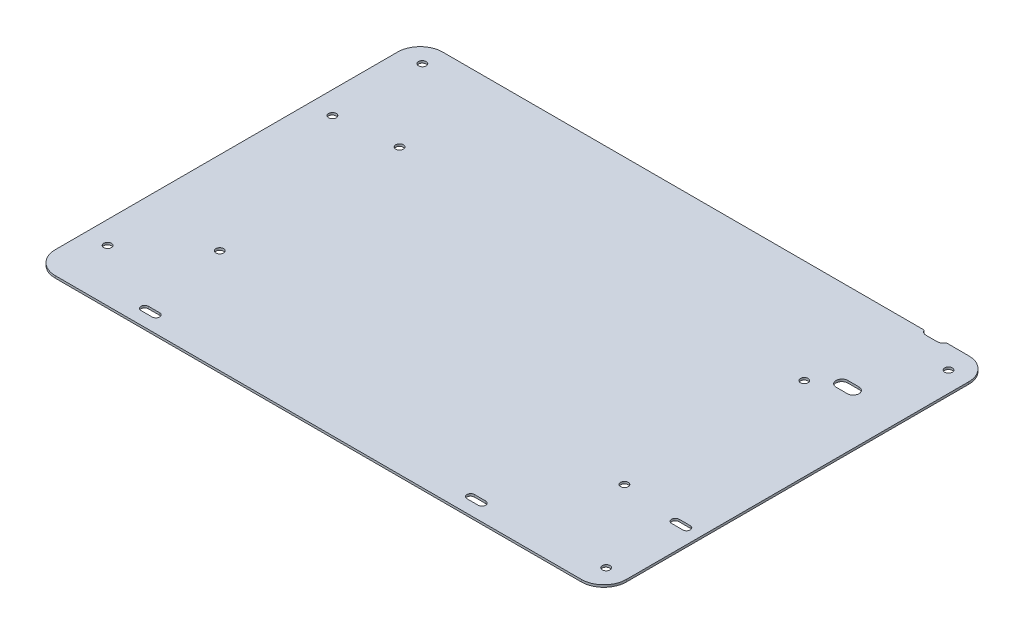
SolidWorks part; units mm, degrees
ref_plane "Front Plane" through (0, 0, 0) normal (0, 0, 1) x (1, 0, 0)
ref_plane "Top Plane" through (0, 0, 0) normal (0, 1, 0) x (1, 0, 0)
ref_plane "Right Plane" through (0, 0, 0) normal (1, 0, 0) x (0, 0, -1)
sketch "Sketch1" plane through (0, 0, 0) normal (0, 1, 0) x (1, 0, 0)
  line L1 (-127, 86.135) -> (127, 86.135)
  line L2 (-127, 86.135) -> (-127, -86.135)
  line L3 (-127, -86.135) -> (127, -86.135)
  line L4 (127, 86.135) -> (127, -86.135)
  line L5 (-127, 86.135) -> (127, -86.135) construction
  line L6 (-127, -86.135) -> (127, 86.135) construction
  point P0 (0, 0)
  dimension "D1" = 254
  dimension "D2" = 172.27
extrude "Boss-Extrude1" add sketch "Sketch1" along normal blind 1
fillet "Fillet1" radius 10 4 edges at (-127, 0.5, 86.135) (127, 0.5, 86.135) (127, 0.5, -86.135) (-127, 0.5, -86.135)
hole_wizard "M3 Clearance Hole1" positions "Sketch2" profile "Sketch3" hole size "M3" standard "ANSI Metric" end condition through all
sketch "Sketch2" plane through (0, 1, 0) normal (0, 1, 0) x (1, 0, 0)
  line L1 (-90, 40) -> (90, 40)
  line L2 (-90, 40) -> (-90, -40)
  line L3 (-90, -40) -> (90, -40)
  line L4 (90, 40) -> (90, -40)
  line L5 (-90, 40) -> (90, -40) construction
  line L6 (-90, -40) -> (90, 40) construction
  line L7 (117, 86.135) -> (-117, 86.135) construction
  line L8 (-127, 76.135) -> (-127, -76.135) construction
  line L9 (-117, -86.135) -> (117, -86.135) construction
  line L10 (127, -76.135) -> (127, 76.135) construction
  point P0 (-117, 77.135)
  point P2 (-117, -62.865)
  point P4 (118, -76.135)
  point P6 (118, 76.135)
  point P8 (-90, -40)
  point P10 (90, -40)
  point P13 (-90, 40)
  point P15 (90, 40)
  point P142 (-117, 37.135)
  dimension "D1" = 180
  dimension "D2" = 80
  dimension "D3" = 9
  dimension "D4" = 10
  dimension "D5" = 10
  dimension "D6" = 23.27
  dimension "D7" = 10
  dimension "D8" = 9
  dimension "D9" = 9
  dimension "D10" = 10
  dimension "D11" = 40
sketch "Sketch3" plane through (-117, 1, -77.135) normal (1, 0, 0) x (0, 0, 1)
  line L0 (0, 0) -> (0, 1)
  line L1 (0, 1) -> (1.7, 1)
  line L2 (1.7, 1) -> (1.7, 0)
  line L5 (1.7, 0) -> (0, 0)
  line L11 (0, -6.35) -> (0, 107.95) construction
  dimension "Thru Hole Dia." = 3.4
  dimension "Thru Hole Depth" = 1
sketch "Sketch4" plane through (0, 1, 0) normal (0, 1, 0) x (1, 0, 0)
  line L0 (-117, 78.835) -> (-114.5685, 78.835)
  line L5 (-117, 75.435) -> (-114.5685, 75.435)
  line L7 (118, 77.835) -> (120.4315, 77.835)
  line L8 (118, 74.435) -> (120.4315, 74.435)
  line L9 (118, -74.435) -> (120.6815, -74.435)
  line L10 (118, -77.835) -> (120.6815, -77.835)
  line L11 (-117, -61.165) -> (-114.5685, -61.165)
  line L12 (-117, -64.565) -> (-114.5685, -64.565)
  circle A1 centre (-117, -62.865) radius 1.7 construction
  circle A3 centre (-112.25, 77.135) radius 2.875
  circle A6 centre (-112.25, -62.865) radius 2.875
  circle A7 centre (123, -76.135) radius 2.875
  circle A8 centre (122.75, 76.135) radius 2.875
  circle A9 centre (-117, 77.135) radius 1.7 construction
  circle A10 centre (118, 76.135) radius 1.7 construction
  circle A11 centre (118, -76.135) radius 1.7 construction
  point P2 (-117, 77.135)
  point P3 (-117, -62.865)
  point P6 (118, -76.135)
  point P10 (118, 76.135)
  circle M1 centre (-117, 77.135) radius 1.7
  circle M2 centre (-117, -62.865) radius 1.7
  circle M3 centre (118, -76.135) radius 1.7
  circle M4 centre (118, 76.135) radius 1.7
  dimension "D2" = 5.75
  dimension "D1" = 4.75
  dimension "D3" = 4.75
  dimension "D4" = 5
  dimension "D5" = 4.75
extrude "Cut-Extrude1" [suppressed] cut sketch "Sketch4" against normal through all contours A3 L0 L5 M1 | A3 | A8 L7 L8 M4 | A8 | A7 L9 L10 M3 | A7 | A6 L11 L12 M2 | A6
sketch "Sketch6" plane through (0, 1, 0) normal (0, 1, 0) x (1, 0, 0)
  line L0 (99.6, 89.735) -> (104.6, 89.735) construction
  line L3 (104.6, 84.535) -> (99.6, 84.535) construction
  line L4 (-127, 76.135) -> (-127, -76.135)
  line L5 (-117, -86.135) -> (117, -86.135)
  line L6 (127, -76.135) -> (127, 76.135)
  line L7 (117, 86.135) -> (-117, 86.135)
  line L8 (-127, 76.135) -> (-127, -76.135)
  line L9 (-117, -86.135) -> (117, -86.135)
  line L10 (127, -76.135) -> (127, 76.135)
  line L11 (117, 86.135) -> (-117, 86.135)
  line L12 (104.6, 44.535) -> (99.6, 44.535) construction
  line L13 (99.6, 49.735) -> (104.6, 49.735) construction
  line L14 (99.6, 89.735) -> (104.6, 89.735)
  line L15 (104.6, 84.535) -> (99.6, 84.535)
  line L16 (104.6, 44.535) -> (99.6, 44.535)
  line L17 (99.6, 49.735) -> (104.6, 49.735)
  line L18 (-84.5, -77.215) -> (-79.5, -77.215) construction
  line L19 (-79.5, -80.515) -> (-84.5, -80.515) construction
  line L20 (60.5, -77.215) -> (65.5, -77.215) construction
  line L21 (65.5, -80.515) -> (60.5, -80.515) construction
  line L22 (120.5, -44.515) -> (115.5, -44.515) construction
  line L23 (115.5, -41.215) -> (120.5, -41.215) construction
  line L24 (-84.5, -77.215) -> (-79.5, -77.215)
  line L25 (-79.5, -80.515) -> (-84.5, -80.515)
  line L26 (60.5, -77.215) -> (65.5, -77.215)
  line L27 (65.5, -80.515) -> (60.5, -80.515)
  line L28 (120.5, -44.515) -> (115.5, -44.515)
  line L29 (115.5, -41.215) -> (120.5, -41.215)
  arc A2 (99.6, 89.735) -> (99.6, 84.535) centre (99.6, 87.135) ccw construction
  arc A3 (104.6, 84.535) -> (104.6, 89.735) centre (104.6, 87.135) ccw construction
  arc A4 (-127, -76.135) -> (-117, -86.135) centre (-117, -76.135) ccw
  arc A5 (117, -86.135) -> (127, -76.135) centre (117, -76.135) ccw
  arc A6 (127, 76.135) -> (117, 86.135) centre (117, 76.135) ccw
  arc A7 (-117, 86.135) -> (-127, 76.135) centre (-117, 76.135) ccw
  arc A8 (-127, -76.135) -> (-117, -86.135) centre (-117, -76.135) ccw
  arc A9 (117, -86.135) -> (127, -76.135) centre (117, -76.135) ccw
  arc A10 (127, 76.135) -> (117, 86.135) centre (117, 76.135) ccw
  arc A11 (-117, 86.135) -> (-127, 76.135) centre (-117, 76.135) ccw
  arc A12 (99.6, 49.735) -> (99.6, 44.535) centre (99.6, 47.135) ccw construction
  arc A13 (104.6, 44.535) -> (104.6, 49.735) centre (104.6, 47.135) ccw construction
  arc A14 (99.6, 89.735) -> (99.6, 84.535) centre (99.6, 87.135) ccw
  arc A15 (104.6, 84.535) -> (104.6, 89.735) centre (104.6, 87.135) ccw
  arc A16 (99.6, 49.735) -> (99.6, 44.535) centre (99.6, 47.135) ccw
  arc A17 (104.6, 44.535) -> (104.6, 49.735) centre (104.6, 47.135) ccw
  arc A18 (-84.5, -77.215) -> (-84.5, -80.515) centre (-84.5, -78.865) ccw construction
  arc A19 (-79.5, -80.515) -> (-79.5, -77.215) centre (-79.5, -78.865) ccw construction
  arc A20 (60.5, -77.215) -> (60.5, -80.515) centre (60.5, -78.865) ccw construction
  arc A21 (65.5, -80.515) -> (65.5, -77.215) centre (65.5, -78.865) ccw construction
  arc A22 (115.5, -41.215) -> (115.5, -44.515) centre (115.5, -42.865) ccw construction
  arc A23 (120.5, -44.515) -> (120.5, -41.215) centre (120.5, -42.865) ccw construction
  arc A24 (-84.5, -77.215) -> (-84.5, -80.515) centre (-84.5, -78.865) ccw
  arc A25 (-79.5, -80.515) -> (-79.5, -77.215) centre (-79.5, -78.865) ccw
  arc A26 (60.5, -77.215) -> (60.5, -80.515) centre (60.5, -78.865) ccw
  arc A27 (65.5, -80.515) -> (65.5, -77.215) centre (65.5, -78.865) ccw
  arc A28 (115.5, -41.215) -> (115.5, -44.515) centre (115.5, -42.865) ccw
  arc A29 (120.5, -44.515) -> (120.5, -41.215) centre (120.5, -42.865) ccw
  dimension "D1" = 0
extrude "Cut-Extrude2" cut sketch "Sketch6" against normal through all contours L25 A25 L24 A24 | L28 A29 L29 A28 | L27 A27 L26 A26 | L16 A17 L17 A16 | L15 A15 L11 A14
equation "\"D3@Sketch4\"=\"D1@Sketch4\""
equation "\"D5@Sketch4\"=\"D1@Sketch4\""
